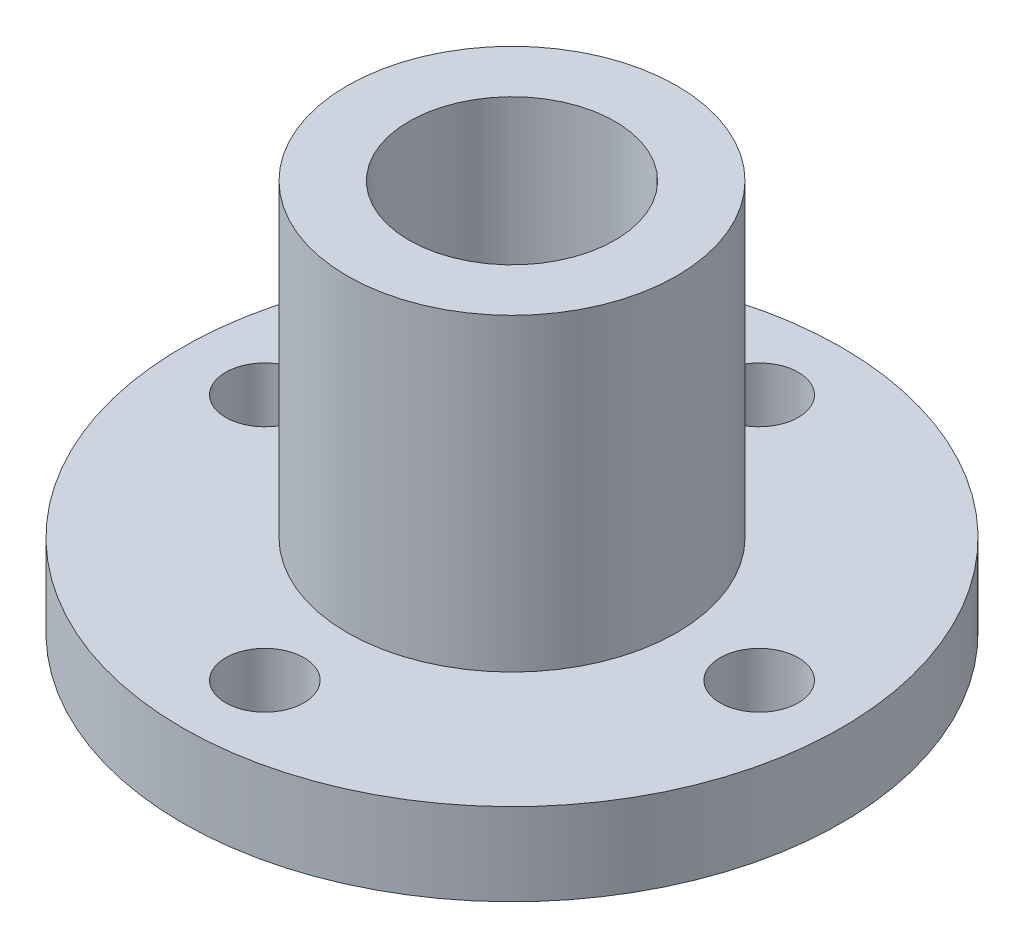
SolidWorks part; units mm, degrees
ref_plane "Front Plane" through (0, 0, 0) normal (0, 0, 1) x (1, 0, 0)
ref_plane "Top Plane" through (0, 0, 0) normal (0, 1, 0) x (1, 0, 0)
ref_plane "Right Plane" through (0, 0, 0) normal (1, 0, 0) x (0, 0, -1)
sketch "Sketch1" plane through (0, 0, 0) normal (0, 1, 0) x (1, 0, 0)
  circle A0 centre (0, 0) radius 16
  dimension "D1" = 32
extrude "Boss-Extrude1" add sketch "Sketch1" along normal blind 4
sketch "Sketch2" plane through (0, 0, 0) normal (0, 1, 0) x (1, 0, 0)
  circle A1 centre (0, 0) radius 8
  dimension "D1" = 16
extrude "Boss-Extrude2" add sketch "Sketch2" along normal blind 19
sketch "Sketch3" plane through (0, 0, 0) normal (0, 1, 0) x (1, 0, 0)
  circle A0 centre (-12, 0) radius 1.9
  point P2 (-10.8431, 2.9993)
  dimension "D1" = 3.8
  dimension "D2" = 12
  dimension "D3" = 0
extrude "Cut-Extrude4" cut sketch "Sketch3" along normal up to next
pattern_circular "CirPattern1" count 4 over 360 about axis through (0, 0, 0) along (0, 1, 0) of "Cut-Extrude4"
sketch "Sketch4" plane through (0, 0, 0) normal (0, 1, 0) x (1, 0, 0)
  circle A0 centre (0, 0) radius 5
  dimension "D1" = 10
extrude "Cut-Extrude6" cut sketch "Sketch4" along normal up to next
